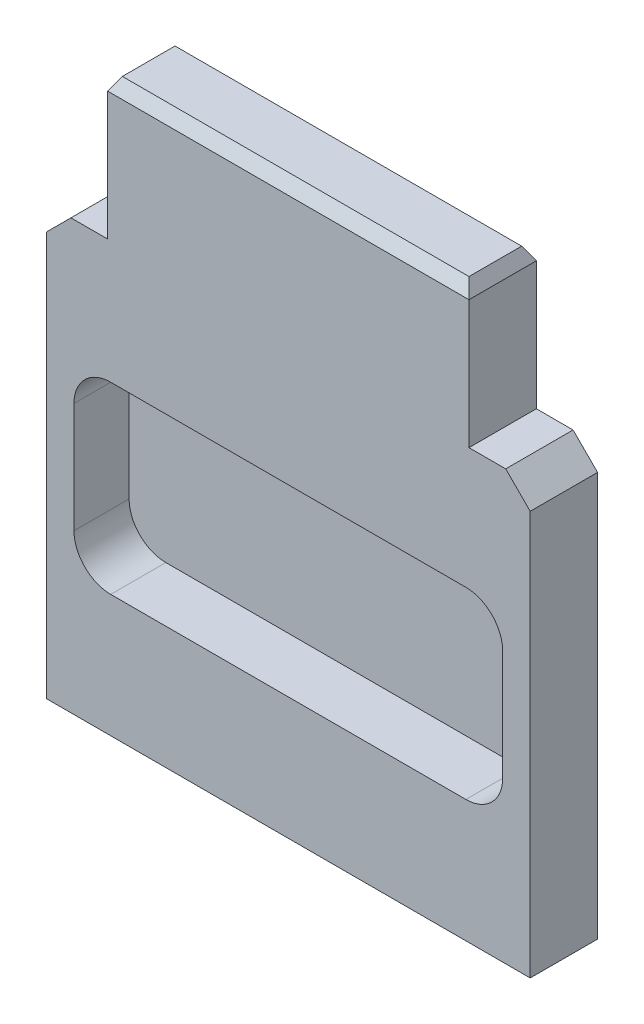
SolidWorks part; units mm, degrees
ref_plane "Спереди" through (0, 0, 0) normal (0, 0, 1) x (1, 0, 0)
ref_plane "Сверху" through (0, 0, 0) normal (0, 1, 0) x (1, 0, 0)
ref_plane "Справа" through (0, 0, 0) normal (1, 0, 0) x (0, 0, -1)
sketch "Эскиз1" plane through (0, 0, 0) normal (0, 0, 1) x (1, 0, 0)
  line L0 (0, 0) -> (0, 45740.3841) construction
  line L1 (19.75, 0) -> (-19.75, 0)
  line L2 (-19.75, 0) -> (-19.75, 33)
  line L3 (-19.75, 33) -> (-17.75, 35)
  line L4 (-14.75, 35) -> (-14.75, 46.5)
  line L5 (-14.75, 46.5) -> (14.75, 46.5)
  line L6 (-17.75, 35) -> (-14.75, 35)
  line L7 (17.75, 35) -> (14.75, 35)
  line L8 (14.75, 35) -> (14.75, 46.5)
  line L9 (19.75, 33) -> (17.75, 35)
  line L10 (19.75, 0) -> (19.75, 33)
  point P3 (-17.934, 46.9743)
  point P9 (27.6524, 0)
  point P15 (0, 0)
  dimension "D1" = 29.5
  dimension "D2" = 11.5
  dimension "D3" = 39.5
  dimension "D4" = 45
  dimension "D5" = 3
  dimension "D6" = 35
extrude "Бобышка-Вытянуть1" add sketch "Эскиз1" along normal blind 5.5
chamfer "Фаска1" distance 0.6 angle 60 4 edges at (14.75, 46.5, 2.75) (0, 46.5, 5.5) (-14.75, 46.5, 2.75) (0, 46.5, 0)
sketch "Эскиз2" plane through (0, 0, 5.5) normal (0, 0, 1) x (1, 0, 0)
  line L0 (0, 0) -> (0, 50000) construction
  line L1 (17.75, 35) -> (14.75, 35) construction
  line L2 (17.5, 10) -> (-17.5, 10)
  line L3 (17.5, 10) -> (17.5, 25)
  line L4 (17.5, 25) -> (-17.5, 25)
  line L5 (-17.5, 10) -> (-17.5, 25)
  line L6 (17.5, 10) -> (-17.5, 25) construction
  line L7 (17.5, 25) -> (-17.5, 10) construction
  point P3 (0, 17.5)
  dimension "D1" = 15
  dimension "D2" = 35
  dimension "D3" = 10
extrude "Вырез-Вытянуть1" cut sketch "Эскиз2" against normal offset from surface (4.5 mm away) 1 up to face at (0, 29.6922, 0)
fillet "Скругление1" radius 3 4 edges at (17.5, 10, 3.25) (-17.5, 10, 3.25) (-17.5, 25, 3.25) (17.5, 25, 3.25)
sketch "Эскиз3" plane through (0, 0, 0) normal (0, -1, 0) x (1, 0, 0)
  line L0 (-19.75, 0) -> (19.75, 0) construction
  circle A0 centre (0, 2.5) radius 1
  point P4 (0, 0)
  dimension "D2" = 2
  dimension "D1" = 2.5
extrude "Бобышка-Вытянуть2" add sketch "Эскиз3" along normal blind 1.5
equation "\"D2@Эскиз1\"=6+5+0.5"
